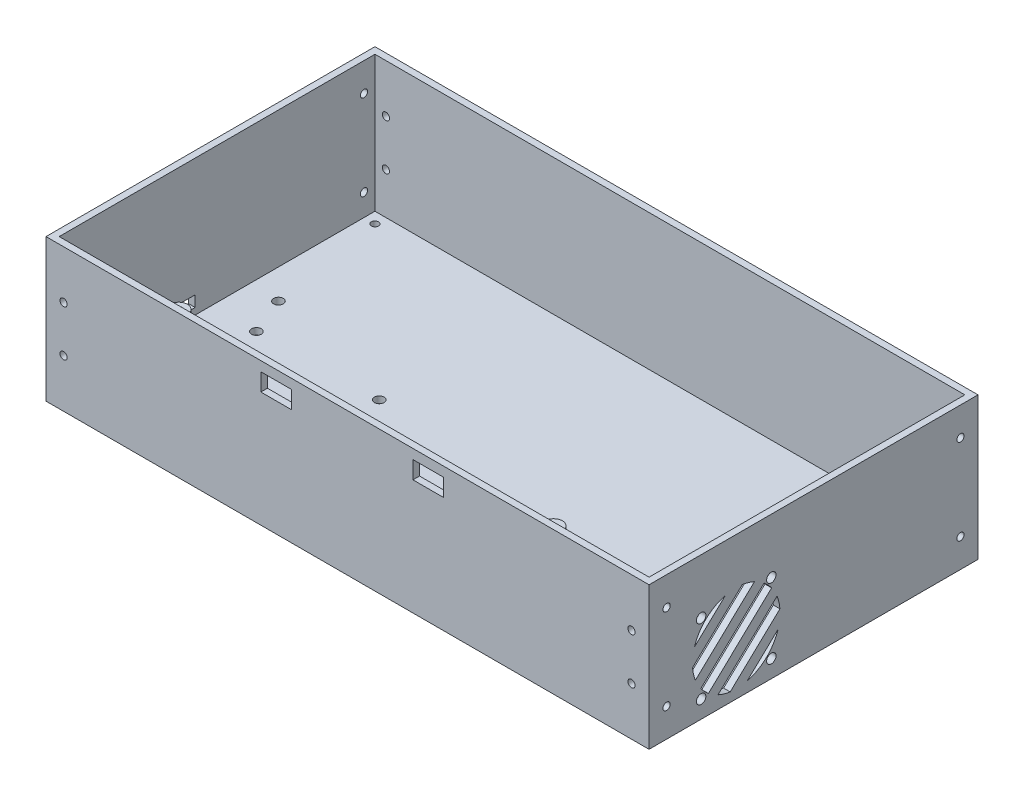
SolidWorks part; units mm, degrees
ref_plane "Ebene vorne" through (0, 0, 0) normal (0, 0, 1) x (1, 0, 0)
ref_plane "Ebene oben" through (0, 0, 0) normal (0, 1, 0) x (1, 0, 0)
ref_plane "Ebene rechts" through (0, 0, 0) normal (1, 0, 0) x (0, 0, -1)
sketch "Skizze1" plane through (0, 0, 0) normal (0, 1, 0) x (1, 0, 0)
  line L1 (-137.5, -75) -> (137.5, -75)
  line L2 (-137.5, -75) -> (-137.5, 75)
  line L3 (-137.5, 75) -> (137.5, 75)
  line L4 (137.5, -75) -> (137.5, 75)
  line L5 (-137.5, -75) -> (137.5, 75) construction
  line L6 (-137.5, 75) -> (137.5, -75) construction
  point P0 (0, 0)
  dimension "D1" = 275
  dimension "D2" = 150
extrude "Aufsatz-Linear austragen1" add sketch "Skizze1" along normal blind 3
sketch "Skizze2" plane through (0, 3, 0) normal (0, 1, 0) x (1, 0, 0)
  line L0 (137.5, -75) -> (137.5, 75) construction
  line L1 (-137.5, 75) -> (137.5, 75)
  line L2 (-137.5, 75) -> (-137.5, 72)
  line L3 (-137.5, 72) -> (137.5, 72)
  line L4 (137.5, 75) -> (137.5, 72)
  line L5 (-137.5, 75) -> (137.5, 72) construction
  line L6 (-137.5, 72) -> (137.5, 75) construction
  line L7 (-137.5, -75) -> (137.5, -75) construction
  line L8 (137.5, 75) -> (134.5, 75)
  line L9 (137.5, 75) -> (137.5, -75)
  line L10 (137.5, -75) -> (134.5, -75)
  line L11 (134.5, 75) -> (134.5, -75)
  line L12 (137.5, 75) -> (134.5, -75) construction
  line L13 (137.5, -75) -> (134.5, 75) construction
  line L14 (-137.5, 75) -> (-137.5, -75) construction
  line L15 (137.5, -75) -> (-137.5, -75)
  line L16 (137.5, -75) -> (137.5, -72)
  line L17 (137.5, -72) -> (-137.5, -72)
  line L18 (-137.5, -75) -> (-137.5, -72)
  line L19 (137.5, -75) -> (-137.5, -72) construction
  line L20 (137.5, -72) -> (-137.5, -75) construction
  line L22 (-137.5, -75) -> (-134.5, -75)
  line L23 (-137.5, -75) -> (-137.5, 75)
  line L24 (-137.5, 75) -> (-134.5, 75)
  line L25 (-134.5, -75) -> (-134.5, 75)
  line L26 (-137.5, -75) -> (-134.5, 75) construction
  line L27 (-137.5, 75) -> (-134.5, -75) construction
  point P4 (0, 73.5)
  point P11 (136, 0)
  point P17 (0, -73.5)
  point P22 (-136, 0)
  line M2 (137.5, -75) -> (137.5, 75)
  line M3 (137.5, 75) -> (-137.5, 75)
  line M4 (-137.5, 75) -> (-137.5, -75)
  line M5 (-137.5, -75) -> (137.5, -75)
  dimension "D1" = 3
  dimension "D2" = 3
  dimension "D3" = 3
  dimension "D4" = 3
extrude "Aufsatz-Linear austragen2" add sketch "Skizze2" along normal blind 62 contours L17 L25 L3 M4 | L25 L3 L11 L1 | L3 L25 M3 M4 | L17 L9 L3 L11 | L11 L3 M3 M2 | L25 L15 L11 L17 | L17 L11 M2 M5 | L25 L17 M5 M4
sketch "Skizze5" plane through (0, 3, 0) normal (0, 1, 0) x (1, 0, 0)
  line L1 (-110, 39) -> (110, 39)
  line L2 (-110, 39) -> (-110, 19)
  line L3 (-110, 19) -> (110, 19)
  line L4 (110, 39) -> (110, 19)
  line L5 (-110, 39) -> (110, 19) construction
  line L6 (-110, 19) -> (110, 39) construction
  line L8 (-110, 19) -> (-110, 39)
  line L11 (-110, 59) -> (-132, 59)
  line L12 (-110, 59) -> (-110, 7)
  line L14 (110, 19) -> (110, 39)
  line L17 (110, 59) -> (132, 59)
  line L18 (110, 59) -> (110, 7)
  line L19 (-110, 7) -> (-132, 7)
  line L20 (-132, 59) -> (-132, 7)
  line L21 (-110, 59) -> (-132, 7) construction
  line L22 (-110, 7) -> (-132, 59) construction
  line L23 (110, 7) -> (132, 7)
  line L24 (132, 59) -> (132, 7)
  line L25 (110, 59) -> (132, 7) construction
  line L26 (110, 7) -> (132, 59) construction
  line L27 (-134.5, 72) -> (134.5, 72) construction
  line L28 (-134.5, 72) -> (134.5, 72) construction
  line L30 (-128, 6.5) -> (-48, 6.5)
  line L31 (-128, 6.5) -> (-128, -31.5)
  line L32 (-128, -31.5) -> (-48, -31.5)
  line L33 (-48, 6.5) -> (-48, -31.5)
  line L34 (-128, 6.5) -> (-48, -31.5) construction
  line L35 (-128, -31.5) -> (-48, 6.5) construction
  line L36 (-25, 4) -> (25, 4)
  line L37 (-25, 4) -> (-25, 54)
  line L38 (-25, 54) -> (25, 54)
  line L39 (25, 4) -> (25, 54)
  line L40 (-25, 4) -> (25, 54) construction
  line L41 (-25, 54) -> (25, 4) construction
  line L42 (-51.3273, -49.5) -> (-93.3273, -49.5)
  line L43 (-51.3273, -49.5) -> (-51.3273, -13.5)
  line L44 (-51.3273, -13.5) -> (-93.3273, -13.5)
  line L45 (-93.3273, -49.5) -> (-93.3273, -13.5)
  line L46 (-51.3273, -49.5) -> (-93.3273, -13.5) construction
  line L47 (-51.3273, -13.5) -> (-93.3273, -49.5) construction
  point P4 (0, 29)
  point P12 (-121, 33)
  point P15 (121, 33)
  point P23 (-88, -12.5)
  point P24 (0, 29)
  point P33 (-72.3273, -31.5)
  dimension "D1" = 220
  dimension "D2" = 22
  dimension "D3" = 22
  dimension "D4" = 20
  dimension "D5" = 52
  dimension "D6" = 52
  dimension "D7" = 13
  dimension "D8" = 13
  dimension "D9" = 12
  dimension "D10" = 38
  dimension "D11" = 0.5
  dimension "D12" = 80
  dimension "D13" = 50
  dimension "D14" = 50
  dimension "D15" = 4
  dimension "D16" = 42
  dimension "D17" = 56
  dimension "D18" = 36
sketch "Skizze7" plane through (0, 3, 0) normal (0, 1, 0) x (1, 0, 0)
  line L0 (134.5, -72) -> (-134.5, -72) construction
  line L1 (-90.125, 29) -> (90.125, 29)
  line L2 (-90.125, 29) -> (-90.125, -71)
  line L3 (-90.125, -71) -> (90.125, -71)
  line L4 (90.125, 29) -> (90.125, -71)
  line L5 (-90.125, 29) -> (90.125, -71) construction
  line L6 (-90.125, -71) -> (90.125, 29) construction
  point P4 (0, -21)
  dimension "D1" = 180.25
  dimension "D2" = 90.125
  dimension "D3" = 100
  dimension "D4" = 1
sketch "Skizze3" plane through (0, 3, 0) normal (0, 1, 0) x (1, 0, 0)
  line L2 (-90.125, 29) -> (-90.125, -71) construction
  line L4 (-90.125, -71) -> (90.125, -71) construction
  circle A0 centre (-85.5, -66.5) radius 4
  circle A1 centre (85.5, -66.5) radius 4
  dimension "D4" = 8
  dimension "D5" = 8
  dimension "D6" = 4.5
  dimension "D1" = 171
  dimension "D2" = 4.625
  dimension "D3" = 4.5
extrude "Aufsatz-Linear austragen3" add sketch "Skizze3" along normal blind 55
sketch "Skizze4" plane through (0, 58, 0) normal (0, 1, 0) x (1, 0, 0)
  circle A0 centre (-85.5, -66.5) radius 1.55
  circle A1 centre (85.5, -66.5) radius 1.55
  dimension "D1" = 3.1
  dimension "D2" = 3.1
extrude "Schnitt-Linear austragen1" cut sketch "Skizze4" against normal through all
sketch "Skizze8" plane through (0, 3, 0) normal (0, 1, 0) x (1, 0, 0)
  line L2 (110, 59) -> (110, 7) construction
  line L3 (-110, 19) -> (110, 19) construction
  line L4 (-132, 59) -> (-132, 7) construction
  line L5 (-128, 6.5) -> (-128, -31.5) construction
  line L6 (-128, -31.5) -> (-48, -31.5) construction
  line L10 (-128, 6.5) -> (-48, 6.5) construction
  circle A0 centre (121.5, 15) radius 2.2
  circle A1 centre (-121, 14.5) radius 2.2
  circle A2 centre (-59.0423, -1.5) radius 2.2
  circle A3 centre (-114.0423, -2.5) radius 2.2
  circle A4 centre (-113.5, -27.5) radius 2.2
  dimension "D1" = 4.4
  dimension "D2" = 11.5
  dimension "D3" = 4
  dimension "D4" = 11
  dimension "D5" = 4.5
  dimension "D6" = 14.5
  dimension "D7" = 25
  dimension "D8" = 4
  dimension "D9" = 55
  dimension "D10" = 8
sketch "Skizze9" plane through (0, 3, 0) normal (0, 1, 0) x (1, 0, 0)
  line L0 (-25, 4) -> (25, 4) construction
  line L1 (90.125, 29) -> (90.125, -71) construction
  circle A0 centre (85.625, -4) radius 4 construction
  circle A1 centre (85.625, -4) radius 1.65
  dimension "D1" = 8
  dimension "D4" = 3.3
  dimension "D2" = 8
  dimension "D3" = 4.5
extrude "Schnitt-Linear austragen2" cut sketch "Skizze9" against normal through all
extrude "Schnitt-Linear austragen3" cut sketch "Skizze8" against normal blind 10
sketch "Skizze10" plane through (0, 3, 0) normal (0, 1, 0) x (1, 0, 0)
  line L0 (-137.5, -75) -> (137.5, -75) construction
  line L1 (-137.5, 75) -> (-137.5, -75) construction
  line L2 (137.5, -75) -> (137.5, 75) construction
  line L4 (137.5, 75) -> (-137.5, 75) construction
  circle A0 centre (-129.5, 67) radius 1.65
  circle A1 centre (129.5, 67) radius 1.65
  circle A2 centre (129.5, -67) radius 1.65
  circle A3 centre (-129.5, -67) radius 1.65
  dimension "D1" = 3.3
  dimension "D2" = 8
  dimension "D3" = 8
  dimension "D4" = 8
  dimension "D5" = 8
  dimension "D6" = 8
  dimension "D7" = 8
  dimension "D8" = 8
  dimension "D9" = 8
extrude "Schnitt-Linear austragen4" cut sketch "Skizze10" against normal blind 10
sketch "Skizze11" plane through (0, 3, 0) normal (0, 1, 0) x (1, 0, 0)
  line L0 (134.5, 72) -> (134.5, -72) construction
  line L1 (134.5, -15.25) -> (124.5, -15.25)
  line L2 (134.5, -15.25) -> (134.5, -55.25)
  line L3 (134.5, -55.25) -> (124.5, -55.25)
  line L4 (124.5, -15.25) -> (124.5, -55.25)
  line L5 (134.5, -15.25) -> (124.5, -55.25) construction
  line L6 (134.5, -55.25) -> (124.5, -15.25) construction
  circle A0 centre (85.625, -4) radius 1.65 construction
  point P4 (129.5, -35.25)
  dimension "D3" = 11.25
  dimension "D1" = 40
  dimension "D2" = 10
sketch "Skizze12" plane through (137.5, 0, 0) normal (1, 0, 0) x (0, 0, -1)
  line L4 (-60.1657, 10.761) -> (-20.6405, 48.1376)
  line L5 (-60.1657, 10.761) -> (-56.7303, 7.1281)
  line L6 (-35.25, 24) -> (-58.0851, 48.1478) construction
  line L7 (-58.0851, 48.1478) -> (-19.829, 7.6926) construction
  line L8 (-75, 0) -> (75, 0) construction
  line L9 (-44.0543, -8.4014) -> (-2.4076, 30.9814)
  line L10 (-44.0543, -8.4014) -> (-47.4897, -4.7685)
  line L11 (-2.4076, 30.9814) -> (-5.843, 34.6143)
  line L12 (-47.4897, -4.7685) -> (-5.843, 34.6143)
  line L13 (-44.0543, -8.4014) -> (-5.843, 34.6143) construction
  line L14 (-2.4076, 30.9814) -> (-47.4897, -4.7685) construction
  line L15 (-67.7646, 17.3383) -> (-26.7833, 56.092)
  line L16 (-67.7646, 17.3383) -> (-64.3292, 13.7054)
  line L17 (-26.7833, 56.092) -> (-23.3479, 52.4591)
  line L18 (-64.3292, 13.7054) -> (-23.3479, 52.4591)
  line L19 (-67.7646, 17.3383) -> (-23.3479, 52.4591) construction
  line L20 (-26.7833, 56.092) -> (-64.3292, 13.7054) construction
  line L21 (-20.6405, 48.1376) -> (-17.2051, 44.5048)
  line L22 (-56.7303, 7.1281) -> (-17.2051, 44.5048)
  line L23 (-60.1657, 10.761) -> (-17.2051, 44.5048) construction
  line L24 (-20.6405, 48.1376) -> (-56.7303, 7.1281) construction
  line L25 (-51.6561, 5.0502) -> (-15.4138, 39.3225)
  line L26 (-51.6561, 5.0502) -> (-48.2207, 1.4173)
  line L27 (-15.4138, 39.3225) -> (-11.9783, 35.6896)
  line L28 (-48.2207, 1.4173) -> (-11.9783, 35.6896)
  line L29 (-51.6561, 5.0502) -> (-11.9783, 35.6896) construction
  line L30 (-15.4138, 39.3225) -> (-48.2207, 1.4173) construction
  circle A0 centre (-35.25, 24) radius 20
  circle A1 centre (-19.25, 40) radius 2.15
  circle A2 centre (-19.25, 8) radius 2.15
  circle A3 centre (-51.25, 8) radius 2.15
  circle A4 centre (-51.25, 40) radius 2.15
  point P9 (-38.6854, 27.6329)
  point P11 (-31.8172, 20.3699)
  point P12 (-24.9487, 13.1065)
  point P13 (-45.5562, 34.8987)
  dimension "D1" = 40
  dimension "D22" = 4.3
  dimension "D23" = 32
  dimension "D2" = 5
  dimension "D3" = 5
  dimension "D4" = 9.9967
  dimension "D5" = 24
  dimension "D6" = 5
  dimension "D7" = 90
  dimension "D8" = 0
  dimension "D9" = 5
  dimension "D10" = 90
  dimension "D11" = 90
  dimension "D12" = 90
  dimension "D13" = 9.9961
  dimension "D14" = 10
  dimension "D15" = 5
  dimension "D16" = 32
  dimension "D17" = 32
  dimension "D18" = 32
  dimension "D19" = 32
  dimension "D20" = 16
  dimension "D21" = 16
  dimension "D24" = 32
extrude "Schnitt-Linear austragen5" cut sketch "Skizze12" against normal blind 10 contours L15 A0 | L4 A0 L18 | L25 A0 L22 | L12 A0 L28 | L9 A0 | A4 | L22 A1 | A2 | L25 A3 | L25 A3 | L22 A1
sketch "Skizze13" plane through (-137.5, 0, 0) normal (-1, 0, 0) x (0, 0, 1)
  line L0 (75, 65) -> (75, 0) construction
  line L1 (60, 11) -> (10, 11)
  line L2 (60, 11) -> (60, 6)
  line L3 (60, 6) -> (10, 6)
  line L4 (10, 11) -> (10, 6)
  line L5 (60, 11) -> (10, 6) construction
  line L6 (60, 6) -> (10, 11) construction
  line L7 (-75, 0) -> (75, 0) construction
  point P4 (35, 8.5)
  dimension "D1" = 5
  dimension "D2" = 50
  dimension "D3" = 15
  dimension "D4" = 6
extrude "Schnitt-Linear austragen6" cut sketch "Skizze13" against normal blind 3
sketch "Skizze14" plane through (0, 0, 75) normal (0, 0, 1) x (1, 0, 0)
  line L0 (-81.5, 58) -> (-89.5, 58) construction
  line L1 (-39.525, 60.6) -> (-25.525, 60.6)
  line L2 (-39.525, 60.6) -> (-39.525, 52.6)
  line L3 (-39.525, 52.6) -> (-25.525, 52.6)
  line L4 (-25.525, 60.6) -> (-25.525, 52.6)
  line L5 (-39.525, 60.6) -> (-25.525, 52.6) construction
  line L6 (-39.525, 52.6) -> (-25.525, 60.6) construction
  line L7 (29.825, 60.6) -> (43.825, 60.6)
  line L8 (29.825, 60.6) -> (29.825, 52.6)
  line L9 (29.825, 52.6) -> (43.825, 52.6)
  line L10 (43.825, 60.6) -> (43.825, 52.6)
  line L11 (29.825, 60.6) -> (43.825, 52.6) construction
  line L12 (29.825, 52.6) -> (43.825, 60.6) construction
  point P4 (-32.525, 56.6)
  point P9 (36.825, 56.6)
  dimension "D1" = 14
  dimension "D2" = 8
  dimension "D3" = 14
  dimension "D4" = 8
  dimension "D5" = 53.3
  dimension "D6" = 57.6
  dimension "D7" = 1.4
extrude "Schnitt-Linear austragen7" cut sketch "Skizze14" against normal blind 3
sketch "Skizze16" plane through (137.5, 0, 0) normal (1, 0, 0) x (0, 0, -1)
  line L1 (-72, 65) -> (72, 65)
  line L2 (-72, 65) -> (-72, 0)
  line L3 (-72, 0) -> (72, 0)
  line L4 (72, 65) -> (72, 0)
  line L5 (-72, 65) -> (72, 0) construction
  line L6 (-72, 0) -> (72, 65) construction
  line L9 (75, 65) -> (75, 0) construction
  point P4 (0, 32.5)
  dimension "D2" = 3
sketch "Skizze18" plane through (-137.5, 0, 0) normal (-1, 0, 0) x (0, 0, 1)
  line L1 (-72, 0) -> (72, 0)
  line L2 (-72, 0) -> (-72, 65)
  line L3 (-72, 65) -> (72, 65)
  line L4 (72, 0) -> (72, 65)
  line L5 (-72, 0) -> (72, 65) construction
  line L6 (-72, 65) -> (72, 0) construction
  point P4 (0, 32.5)
sketch "Skizze19" plane through (0, 0, 75) normal (0, 0, 1) x (1, 0, 0)
  line L0 (-137.5, 0) -> (-137.5, 65) construction
  text T0 "<b>COM</b>" font "Century Gothic" height 10
  text T1 "PWR\r\n" font "Century Gothic" height 10
  dimension "D1" = 135
  dimension "D2" = 55
sketch "Skizze20" plane through (0, 3, 0) normal (0, 1, 0) x (1, 0, 0)
  circle A0 centre (0, -41.0626) radius 1.65
  circle A1 centre (20, -41.0626) radius 1.65
  dimension "D1" = 3.3
  dimension "D2" = 3.3
  dimension "D3" = 20
extrude "Schnitt-Linear austragen8" cut sketch "Skizze20" against normal blind 3
sketch "Skizze21" plane through (137.5, 0, 0) normal (1, 0, 0) x (0, 0, -1)
  line L1 (-75, 65) -> (-75, 0) construction
  line L2 (75, 65) -> (75, 0) construction
  line L3 (-72, 65) -> (72, 65) construction
  line L4 (-75, 65) -> (75, 65) construction
  line L5 (-72, 0) -> (72, 0) construction
  circle A0 centre (-67, 52) radius 1.65
  circle A1 centre (-67, 13) radius 1.65
  circle A2 centre (67, 13) radius 1.65
  circle A3 centre (67, 52) radius 1.65
  dimension "D1" = 3.3
  dimension "D2" = 8
  dimension "D3" = 8
  dimension "D4" = 8
  dimension "D5" = 8
  dimension "D6" = 13
  dimension "D7" = 13
  dimension "D8" = 13
  dimension "D9" = 13
extrude "Schnitt-Linear austragen9" cut sketch "Skizze21" against normal blind 3
sketch "Skizze22" plane through (-137.5, 0, 0) normal (-1, 0, 0) x (0, 0, 1)
  line L0 (-75, 65) -> (-75, 0) construction
  line L1 (75, 65) -> (75, 0) construction
  line L2 (72, 65) -> (-72, 65) construction
  line L3 (72, 0) -> (-72, 0) construction
  circle A0 centre (-67, 52) radius 1.65
  circle A1 centre (-67, 13) radius 1.65
  circle A2 centre (67, 13) radius 1.65
  circle A3 centre (67, 52) radius 1.65
  dimension "D1" = 3.3
  dimension "D2" = 8
  dimension "D3" = 8
  dimension "D4" = 8
  dimension "D5" = 8
  dimension "D6" = 13
  dimension "D7" = 13
  dimension "D8" = 13
  dimension "D9" = 13
extrude "Schnitt-Linear austragen10" cut sketch "Skizze22" against normal blind 3
sketch "Skizze23" plane through (0, 0, 75) normal (0, 0, 1) x (1, 0, 0)
  line L0 (-137.5, 0) -> (-137.5, 65) construction
  line L1 (-137.5, 65) -> (-137.5, 0) construction
  line L2 (137.5, 0) -> (137.5, 65) construction
  line L3 (137.5, 65) -> (137.5, 0) construction
  line L4 (-137.5, 0) -> (137.5, 0) construction
  line L5 (-137.5, 65) -> (137.5, 65) construction
  circle A0 centre (-129.495, 43) radius 1.65
  circle A1 centre (-129.5, 22) radius 1.65
  circle A2 centre (129.5, 43) radius 1.65
  circle A3 centre (129.5, 22) radius 1.65
  dimension "D1" = 3.3
  dimension "D2" = 8.005
  dimension "D3" = 8
  dimension "D4" = 8
  dimension "D5" = 8
  dimension "D6" = 22
  dimension "D7" = 22
  dimension "D8" = 22
  dimension "D9" = 22
extrude "Schnitt-Linear austragen11" cut sketch "Skizze23" against normal blind 3
sketch "Skizze24" plane through (0, 0, -75) normal (0, 0, -1) x (-1, 0, 0)
  line L0 (-137.5, 65) -> (-137.5, 0) construction
  line L1 (-137.5, 0) -> (-137.5, 65) construction
  line L2 (137.5, 65) -> (137.5, 0) construction
  line L3 (137.5, 0) -> (137.5, 65) construction
  line L4 (-137.5, 65) -> (137.5, 65) construction
  line L5 (-137.5, 0) -> (137.5, 0) construction
  circle A0 centre (-129.5, 43) radius 1.65
  circle A1 centre (-129.5, 22) radius 1.65
  circle A2 centre (129.5, 43) radius 1.65
  circle A3 centre (129.5, 22) radius 1.65
  dimension "D1" = 3.3
  dimension "D2" = 8
  dimension "D3" = 8
  dimension "D4" = 8
  dimension "D5" = 8
  dimension "D6" = 22
  dimension "D7" = 22
  dimension "D8" = 22
  dimension "D9" = 22
extrude "Schnitt-Linear austragen12" cut sketch "Skizze24" against normal blind 3
sketch "Skizze25" plane through (0, 3, 0) normal (0, 1, 0) x (1, 0, 0)
  line L0 (-134.5, 72) -> (134.5, 72) construction
  line L1 (41.6063, 71) -> (76.6063, 71)
  line L2 (41.6063, 71) -> (41.6063, 50)
  line L3 (41.6063, 50) -> (76.6063, 50)
  line L4 (76.6063, 71) -> (76.6063, 50)
  line L5 (41.6063, 71) -> (76.6063, 50) construction
  line L6 (41.6063, 50) -> (76.6063, 71) construction
  point P4 (59.1063, 60.5)
  dimension "D1" = 1
  dimension "D2" = 21
  dimension "D3" = 35
sketch "Skizze26" plane through (0, 3, 0) normal (0, 1, 0) x (1, 0, 0)
  line L1 (-93, 48.5) -> (93, 48.5)
  line L2 (-93, 48.5) -> (-93, 31.2)
  line L3 (-93, 31.2) -> (93, 31.2)
  line L4 (93, 48.5) -> (93, 31.2)
  line L5 (-93, 48.5) -> (93, 31.2) construction
  line L6 (-93, 31.2) -> (93, 48.5) construction
  line L7 (-93, 48.5) -> (-100, 48.5)
  line L8 (-93, 48.5) -> (-93, 31.2)
  line L9 (-93, 31.2) -> (-100, 31.2)
  line L10 (-100, 48.5) -> (-100, 31.2)
  line L11 (-93, 48.5) -> (-100, 31.2) construction
  line L12 (-93, 31.2) -> (-100, 48.5) construction
  line L13 (93, 43.35) -> (98, 43.35)
  line L14 (93, 43.35) -> (93, 36.35)
  line L15 (93, 36.35) -> (98, 36.35)
  line L16 (98, 43.35) -> (98, 36.35)
  line L17 (93, 43.35) -> (98, 36.35) construction
  line L18 (93, 36.35) -> (98, 43.35) construction
  point P4 (0, 39.85)
  point P7 (-96.5, 39.85)
  point P13 (95.5, 39.85)
  dimension "D1" = 17.3
  dimension "D2" = 186
  dimension "D3" = 1.5
  dimension "D4" = 7
  dimension "D5" = 7
  dimension "D6" = 5
sketch "Skizze27" plane through (0, 3, 0) normal (0, 1, 0) x (1, 0, 0)
  line L1 (-134.5, 72) -> (-124.5, 72)
  line L2 (-134.5, 72) -> (-134.5, 62)
  line L3 (-134.5, 62) -> (-124.5, 62)
  line L4 (-124.5, 72) -> (-124.5, 62)
  line L5 (-134.5, 72) -> (-124.5, 62) construction
  line L6 (-134.5, 62) -> (-124.5, 72) construction
  line L7 (134.5, 72) -> (124.5, 72)
  line L8 (134.5, 72) -> (134.5, 62)
  line L9 (134.5, 62) -> (124.5, 62)
  line L10 (124.5, 72) -> (124.5, 62)
  line L11 (134.5, 72) -> (124.5, 62) construction
  line L12 (134.5, 62) -> (124.5, 72) construction
  point P4 (-129.5, 67)
  point P10 (129.5, 67)
  dimension "D1" = 10
  dimension "D2" = 10
  dimension "D3" = 10
  dimension "D4" = 10
sketch "Skizze28" plane through (0, 3, 0) normal (0, 1, 0) x (1, 0, 0)
  line L1 (124.5, 72) -> (119.5, 72)
  line L2 (124.5, 72) -> (124.5, 62)
  line L3 (124.5, 62) -> (119.5, 62)
  line L4 (119.5, 72) -> (119.5, 62)
  line L5 (124.5, 72) -> (119.5, 62) construction
  line L6 (124.5, 62) -> (119.5, 72) construction
  line L7 (119.5, 62) -> (124.5, 62)
  line L8 (119.5, 62) -> (119.5, 32)
  line L9 (119.5, 32) -> (124.5, 32)
  line L10 (124.5, 62) -> (124.5, 32)
  line L11 (119.5, 62) -> (124.5, 32) construction
  line L12 (119.5, 32) -> (124.5, 62) construction
  line L13 (119.5, 41.35) -> (98, 41.35)
  line L14 (119.5, 41.35) -> (119.5, 38.35)
  line L15 (119.5, 38.35) -> (98, 38.35)
  line L16 (98, 41.35) -> (98, 38.35)
  line L17 (119.5, 41.35) -> (98, 38.35) construction
  line L18 (119.5, 38.35) -> (98, 41.35) construction
  point P4 (122, 67)
  point P8 (122, 47)
  point P14 (108.75, 39.85)
  dimension "D1" = 10
  dimension "D2" = 5
  dimension "D3" = 30
  dimension "D4" = 3
  dimension "D5" = 20.65
sketch "Skizze29" plane through (0, 3, 0) normal (0, 1, 0) x (1, 0, 0)
  line L0 (-93, 31.2) -> (-100, 31.2) construction
  line L1 (-100, 24.25) -> (-102.7545, 24.25)
  line L2 (-100, 24.25) -> (-100, 55.45)
  line L3 (-100, 55.45) -> (-102.7545, 55.45)
  line L4 (-102.7545, 24.25) -> (-102.7545, 55.45)
  line L5 (-100, 24.25) -> (-102.7545, 55.45) construction
  line L6 (-100, 55.45) -> (-102.7545, 24.25) construction
  line L8 (-116.3, 33.85) -> (-114, 33.85)
  line L9 (-102.7545, 56.75) -> (-132.5, 56.75)
  line L10 (-102.7545, 56.75) -> (-102.7545, 33.85)
  line L11 (-102.7545, 33.85) -> (-132.5, 33.85)
  line L12 (-132.5, 56.75) -> (-132.5, 33.85)
  line L13 (-102.7545, 56.75) -> (-132.5, 33.85) construction
  line L14 (-102.7545, 33.85) -> (-132.5, 56.75) construction
  line L15 (-114, 56.75) -> (-116.3, 56.75)
  line L16 (-114, 56.75) -> (-114, 61.75)
  line L17 (-114, 61.75) -> (-116.3, 61.75)
  line L18 (-116.3, 56.75) -> (-116.3, 61.75)
  line L19 (-114, 56.75) -> (-116.3, 61.75) construction
  line L20 (-114, 61.75) -> (-116.3, 56.75) construction
  line L21 (-116.3, 33.85) -> (-116.3, 28.85)
  line L22 (-116.3, 28.85) -> (-114, 28.85)
  line L23 (-114, 33.85) -> (-114, 28.85)
  line L24 (-116.3, 33.85) -> (-114, 28.85) construction
  line L25 (-116.3, 28.85) -> (-114, 33.85) construction
  point P4 (-101.3773, 39.85)
  point P11 (-117.6273, 45.3)
  point P16 (-115.15, 59.25)
  point P22 (-115.15, 31.35)
  dimension "D1" = 8.65
  dimension "D2" = 31.2
  dimension "D3" = 22.9
  dimension "D4" = 2.3
  dimension "D5" = 5
  dimension "D6" = 6
  dimension "D7" = 5
  dimension "D8" = 32.5
  dimension "D9" = 16.2
  dimension "D10" = 16.2
  dimension "D11" = 2.3
